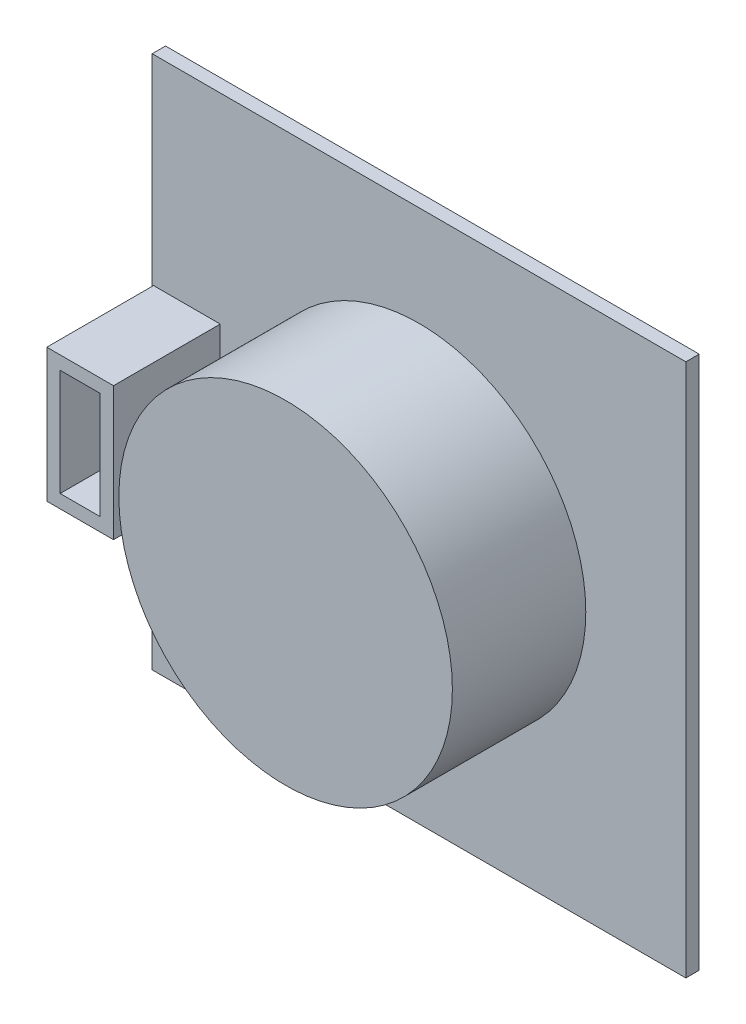
SolidWorks part; units mm, degrees
ref_plane "Plan de face" through (0, 0, 0) normal (0, 0, 1) x (1, 0, 0)
ref_plane "Plan de dessus" through (0, 0, 0) normal (0, 1, 0) x (1, 0, 0)
ref_plane "Plan de droite" through (0, 0, 0) normal (1, 0, 0) x (0, 0, -1)
sketch "Esquisse1" plane through (0, 0, 0) normal (0, 0, 1) x (1, 0, 0)
  line L1 (0, 0) -> (4, 0)
  line L2 (0, 0) -> (0, 4)
  line L3 (0, 4) -> (4, 4)
  line L4 (4, 0) -> (4, 4)
  dimension "D1" = 4
  dimension "D2" = 4
extrude "Boss.-Extru.1" add sketch "Esquisse1" along normal blind 0.1
sketch "Esquisse2" plane through (0, 0, 0.1) normal (0, 0, 1) x (1, 0, 0)
  line L0 (2, 2) -> (4, 2) construction
  line L1 (4, 0) -> (4, 4) construction
  line L2 (2, 2) -> (2, 4) construction
  line L3 (4, 4) -> (0, 4) construction
  line L4 (2, 2) -> (2, 0) construction
  line L5 (0, 0) -> (4, 0) construction
  circle A0 centre (2, 2) radius 1.25
  dimension "D1" = 2.5
extrude "Boss.-Extru.2" add sketch "Esquisse2" along normal blind 1
sketch "Esquisse4" plane through (0, 0, 0.1) normal (0, 0, 1) x (1, 0, 0)
  line L1 (0.01, 2.5) -> (0.51, 2.5)
  line L2 (0.01, 2.5) -> (0.01, 1.5)
  line L3 (0.01, 1.5) -> (0.51, 1.5)
  line L4 (0.51, 2.5) -> (0.51, 1.5)
  line L5 (0.51, 2.5) -> (0.51, 4) construction
  line L6 (4, 4) -> (0, 4) construction
  line L7 (0.51, 1.5) -> (0.51, 0) construction
  line L8 (0, 0) -> (4, 0) construction
  line L9 (0, 4) -> (0, 0) construction
  dimension "D1" = 0.5
  dimension "D2" = 1
  dimension "D3" = 0.01
extrude "Boss.-Extru.3" add sketch "Esquisse4" along normal blind 0.8
sketch "Esquisse5" plane through (0, 0, 0.9) normal (0, 0, 1) x (1, 0, 0)
  line L0 (0.51, 2.5) -> (0.01, 2.5) construction
  line L1 (0.11, 2.4) -> (0.4096, 2.4)
  line L2 (0.11, 2.4) -> (0.11, 1.6)
  line L3 (0.11, 1.6) -> (0.4096, 1.6)
  line L4 (0.4096, 2.4) -> (0.4096, 1.6)
  line L5 (0.01, 1.5) -> (0.51, 1.5) construction
  line L6 (0.01, 2.5) -> (0.01, 1.5) construction
  line L7 (0.51, 1.5) -> (0.51, 2.5) construction
  dimension "D1" = 0.1
  dimension "D2" = 0.1
  dimension "D3" = 0.1
  dimension "D4" = 0.1004
extrude "Enlèv. mat.-Extru.1" cut sketch "Esquisse5" against normal blind 0.7
